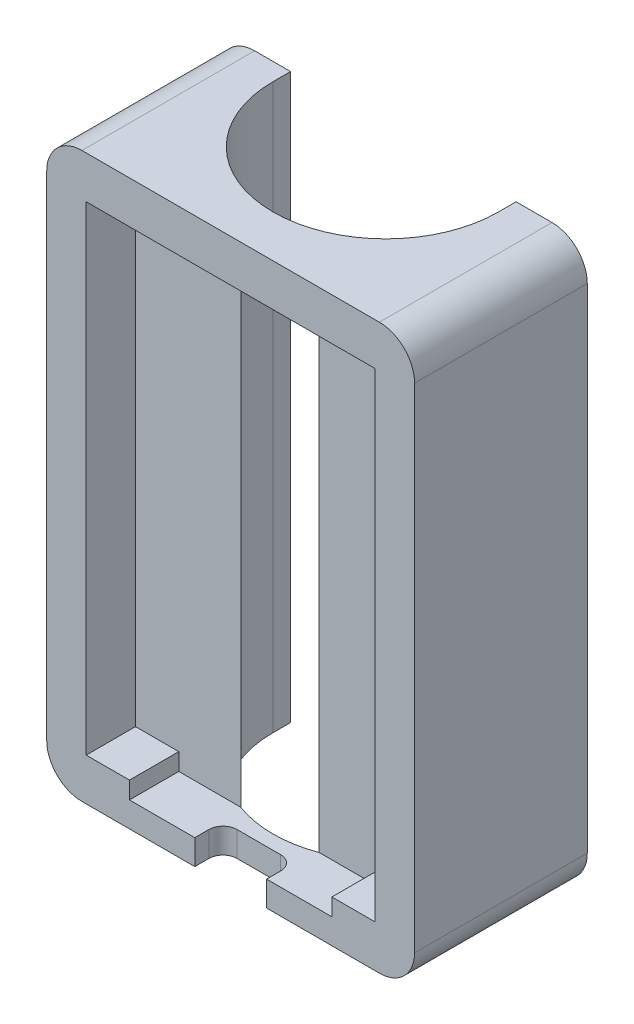
SolidWorks part; units mm, degrees
ref_plane "Plan de face" through (0, 0, 0) normal (0, 0, 1) x (1, 0, 0)
ref_plane "Plan de dessus" through (0, 0, 0) normal (0, 1, 0) x (1, 0, 0)
ref_plane "Plan de droite" through (0, 0, 0) normal (1, 0, 0) x (0, 0, -1)
sketch "Esquisse1" plane through (0, 0, 0) normal (0, 0, 1) x (1, 0, 0)
  line L1 (-41.2248, -2.0065) -> (10.9752, -2.0065)
  line L2 (-41.2248, -2.0065) -> (-41.2248, -82.0065)
  line L3 (-41.2248, -82.0065) -> (10.9752, -82.0065)
  line L4 (10.9752, -2.0065) -> (10.9752, -82.0065)
extrude "Boss.-Extru.2" add sketch "Esquisse1" along normal blind 22
sketch "Esquisse2" plane through (0, -82.0065, 0) normal (0, -1, 0) x (1, 0, 0)
  line L0 (-41.2248, 0) -> (10.9752, 0) construction
  circle A0 centre (-15.1248, 0) radius 16
sketch "Esquisse3" plane through (0, 0, 22) normal (0, 0, 1) x (1, 0, 0)
  line L0 (-41.2248, -2.0065) -> (-41.2248, -82.0065) construction
  line L1 (-39.4848, -5.5677) -> (9.2352, -5.5677)
  line L2 (-39.4848, -5.5677) -> (-39.4848, -78.4453)
  line L3 (-39.4848, -78.4453) -> (9.2352, -78.4453)
  line L4 (9.2352, -5.5677) -> (9.2352, -78.4453)
  line L5 (10.9752, -82.0065) -> (10.9752, -2.0065) construction
  line L6 (10.9752, -2.0065) -> (-41.2248, -2.0065) construction
  line L7 (-31.1248, -82.0065) -> (0.8752, -82.0065) construction
  dimension "D1" = 1.74
  dimension "D2" = 1.74
  dimension "D3" = 3.5612
  dimension "D4" = 3.5612
extrude "Enlèv. mat.-Extru.1" cut sketch "Esquisse3" against normal blind 5
fillet "Congé1" radius 10 4 edges at (-39.4848, -78.4453, 19.5) (9.2352, -78.4453, 19.5) (9.2352, -5.5677, 19.5) (-39.4848, -5.5677, 19.5)
sketch "Esquisse5" plane through (0, 0, 17) normal (0, 0, 1) x (1, 0, 0)
  line L0 (-35.6248, -42.0065) -> (5.3752, -42.0065) construction
  line L1 (-35.6248, -8.0065) -> (5.3752, -8.0065)
  line L2 (-35.6248, -8.0065) -> (-35.6248, -15.5677)
  line L3 (-35.6248, -76.0065) -> (-29.4848, -76.0065)
  line L4 (5.3752, -8.0065) -> (5.3752, -15.5677)
  line L5 (10.9752, -2.0065) -> (-41.2248, -2.0065) construction
  line L6 (5.3752, -68.4453) -> (5.3752, -76.0065)
  line L7 (-0.7648, -76.0065) -> (5.3752, -76.0065)
  line L8 (-29.4848, -8.0065) -> (-0.7648, -8.0065)
  line L9 (10.9752, -82.0065) -> (10.9752, -2.0065) construction
  line L10 (-35.6248, -68.4453) -> (-35.6248, -15.5677)
  line L11 (5.3752, -15.5677) -> (5.3752, -68.4453)
  line L13 (-35.6248, -15.5677) -> (-35.6248, -8.0065)
  line L15 (-29.4848, -8.0065) -> (-35.6248, -8.0065)
  line L16 (-39.4848, -15.5677) -> (-39.4848, -5.5677)
  line L17 (-39.4848, -5.5677) -> (-29.4848, -5.5677)
  line L18 (-15.1248, -8.0065) -> (-15.1248, -76.0065) construction
  line L26 (9.2352, -15.5677) -> (9.2352, -5.5677)
  line L27 (9.2352, -5.5677) -> (-0.7648, -5.5677)
  line L29 (9.2352, -68.4453) -> (9.2352, -78.4453)
  line L30 (9.2352, -78.4453) -> (-0.7648, -78.4453)
  line L31 (-0.7648, -78.4453) -> (-0.7648, -76.0065)
  line L33 (-29.4848, -78.4453) -> (-29.4848, -76.0065)
  line L34 (-39.4848, -78.4453) -> (-29.4848, -78.4453)
  line L35 (-39.4848, -68.4453) -> (-39.4848, -78.4453)
  line L36 (-35.6248, -68.4453) -> (-35.6248, -76.0065)
  line M5 (-39.4848, -15.5677) -> (-39.4848, -68.4453)
  arc M6 (-39.4848, -68.4453) -> (-29.4848, -78.4453) centre (-29.4848, -68.4453) ccw
  arc M8 (-0.7648, -78.4453) -> (9.2352, -68.4453) centre (-0.7648, -68.4453) ccw
  line M9 (9.2352, -68.4453) -> (9.2352, -15.5677)
  arc M10 (9.2352, -15.5677) -> (-0.7648, -5.5677) centre (-0.7648, -15.5677) ccw
  line M11 (-0.7648, -5.5677) -> (-29.4848, -5.5677)
  arc M12 (-29.4848, -5.5677) -> (-39.4848, -15.5677) centre (-29.4848, -15.5677) ccw
  dimension "D1" = 41
  dimension "D2" = 68
  dimension "D3" = 6
  dimension "D4" = 5.6
extrude "Boss.-Extru.4" add sketch "Esquisse5" along normal blind 5 contours L36 L10 L2 L1 L4 L11 L6 L7 L31 L33 L3 M8 M9 M10 M11 M12 M5 M6
extrude "Enlèv. mat.-Extru.3" cut sketch "Esquisse2" against normal through all contours A0
sketch "Esquisse7" plane through (0, 0, 17) normal (0, 0, 1) x (1, 0, 0)
  line L0 (-35.6248, -8.0065) -> (5.3752, -8.0065)
  line L1 (5.3752, -8.0065) -> (5.3752, -76.0065)
  line L2 (5.3752, -76.0065) -> (-0.7648, -76.0065)
  line L3 (-0.7648, -76.0065) -> (-0.7648, -78.4453)
  line L4 (-0.7648, -78.4453) -> (-29.4848, -78.4453)
  line L5 (-29.4848, -78.4453) -> (-29.4848, -76.0065)
  line L6 (-29.4848, -76.0065) -> (-35.6248, -76.0065)
  line L7 (-35.6248, -76.0065) -> (-35.6248, -8.0065)
extrude "Enlèv. mat.-Extru.5" cut sketch "Esquisse7" against normal blind 2
sketch "Esquisse8" plane through (0, 0, 22) normal (0, 0, 1) x (1, 0, 0)
  line L1 (-20.2198, -78.4453) -> (-10.0298, -78.4453)
  line L2 (-20.2198, -78.4453) -> (-20.2198, -82.0065)
  line L3 (-20.2198, -82.0065) -> (-10.0298, -82.0065)
  line L4 (-10.0298, -78.4453) -> (-10.0298, -82.0065)
  line L5 (-29.4848, -78.4453) -> (-29.4848, -76.0065) construction
  line L7 (-0.7648, -78.4453) -> (-0.7648, -76.0065) construction
  dimension "D1" = 9.265
  dimension "D2" = 9.265
extrude "Enlèv. mat.-Extru.6" cut sketch "Esquisse8" against normal blind 4
fillet "Congé3" radius 2 2 edges at (-10.0298, -80.2259, 18) (-20.2198, -80.2259, 18)
sketch "Esquisse9" plane through (0, 0, 0) normal (0, 0, -1) x (-1, 0, 0)
  line L1 (31.1248, -2.0065) -> (41.2248, -2.0065)
  line L2 (31.1248, -2.0065) -> (31.1248, -82.0065)
  line L3 (31.1248, -82.0065) -> (41.2248, -82.0065)
  line L4 (41.2248, -2.0065) -> (41.2248, -82.0065)
  line L5 (-10.9752, -2.0065) -> (-0.8752, -2.0065)
  line L6 (-10.9752, -2.0065) -> (-10.9752, -82.0065)
  line L7 (-10.9752, -82.0065) -> (-0.8752, -82.0065)
  line L8 (-0.8752, -2.0065) -> (-0.8752, -82.0065)
extrude "Boss.-Extru.5" add sketch "Esquisse9" along normal blind 2.5
fillet "Congé4" radius 5 4 edges at (10.9752, -2.0065, 9.75) (10.9752, -82.0065, 9.75) (-41.2248, -82.0065, 9.75) (-41.2248, -2.0065, 9.75)
